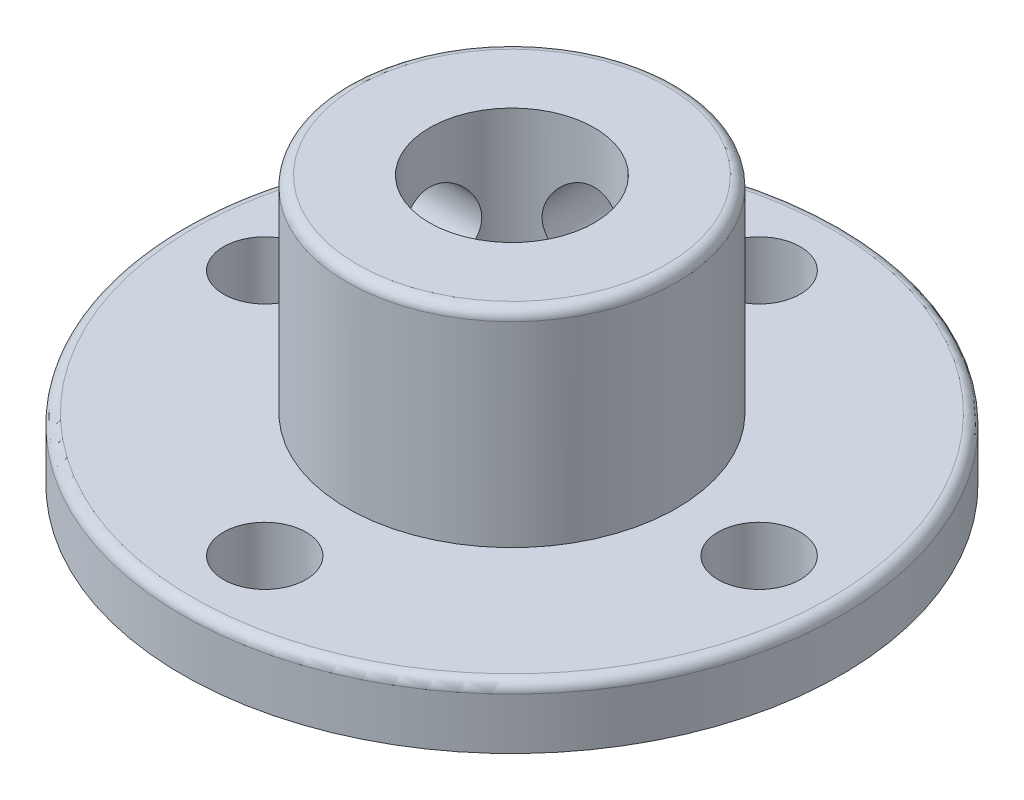
SolidWorks part; units mm, degrees
ref_plane "Front Plane" through (0, 0, 0) normal (0, 0, 1) x (1, 0, 0)
ref_plane "Top Plane" through (0, 0, 0) normal (0, 1, 0) x (1, 0, 0)
ref_plane "Right Plane" through (0, 0, 0) normal (1, 0, 0) x (0, 0, -1)
sketch "Sketch1" plane through (0, 0, 0) normal (0, 1, 0) x (1, 0, 0)
  circle A0 centre (0, 0) radius 4
  circle A1 centre (0, 0) radius 8
  dimension "D1" = 8
  dimension "D2" = 16
extrude "Boss-Extrude1" add sketch "Sketch1" along normal blind 13
sketch "Sketch2" plane through (0, 0, 0) normal (0, 0, 1) x (1, 0, 0)
  line L0 (4, 13) -> (-4, 13) construction
  circle A0 centre (0, 8.5) radius 2
  dimension "D1" = 4
  dimension "D2" = 4.5
extrude "Cut-Extrude1" cut sketch "Sketch2" against normal up to next
sketch "Sketch3" plane through (0, 0, 0) normal (1, 0, 0) x (0, 0, -1)
  line L0 (4, 13) -> (-4, 13) construction
  circle A0 centre (0, 8.5) radius 2
  dimension "D1" = 4
  dimension "D2" = 4.5
extrude "Cut-Extrude2" cut sketch "Sketch3" against normal up to next
sketch "Sketch4" plane through (0, 0, 0) normal (0, -1, 0) x (1, 0, 0)
  circle A0 centre (0, 0) radius 16
  circle A1 centre (0, 0) radius 4 construction
  circle A2 centre (0, 0) radius 4
  dimension "D1" = 32
extrude "Boss-Extrude2" add sketch "Sketch4" against normal blind 3
sketch "Sketch5" plane through (0, 3, 0) normal (0, 1, 0) x (1, 0, 0)
  circle A0 centre (-12, 0) radius 2
  circle A1 centre (0, 12) radius 2
  circle A2 centre (12, 0) radius 2
  circle A3 centre (0, -12) radius 2
  point P11 (0, 0)
  dimension "D1" = 4
  dimension "D2" = 12
extrude "Cut-Extrude3" cut sketch "Sketch5" against normal up to next
fillet "Fillet1" radius 0.5 2 edges at (0, 3, -16) (0, 13, 8)
